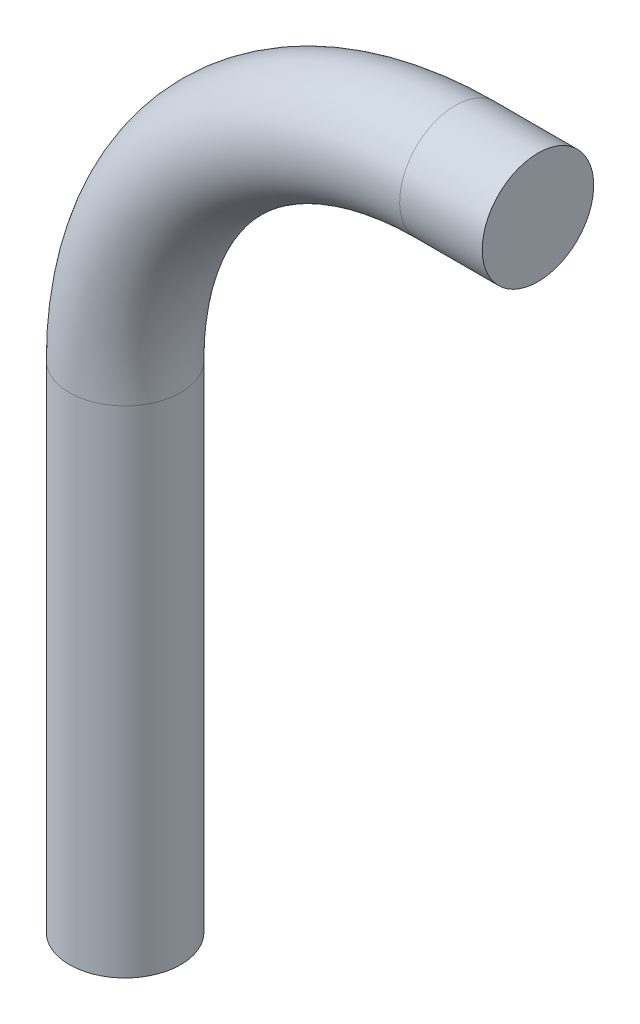
SolidWorks part; units mm, degrees
ref_plane "Front Plane" through (0, 0, 0) normal (0, 0, 1) x (1, 0, 0)
ref_plane "Top Plane" through (0, 0, 0) normal (0, 1, 0) x (1, 0, 0)
ref_plane "Right Plane" through (0, 0, 0) normal (1, 0, 0) x (0, 0, -1)
sketch "Sketch1" plane through (0, 0, 0) normal (0, 0, 1) x (1, 0, 0)
  line L0 (0, 0) -> (0, 60)
  line L1 (40, 100) -> (50, 100)
  arc A0 (0, 60) -> (40, 100) centre (40, 60) cw
  point P6 (0, 100)
  dimension "D3" = 40
  dimension "D1" = 50
  dimension "D2" = 100
  dimension "D4" = 90
sketch "Sketch2" plane through (0, 0, 0) normal (0, 1, 0) x (1, 0, 0)
  circle A0 centre (0, 0) radius 6.75
  dimension "D1" = 13.5
sweep "Sweep1" add profiles "Sketch2" path "Sketch1"
